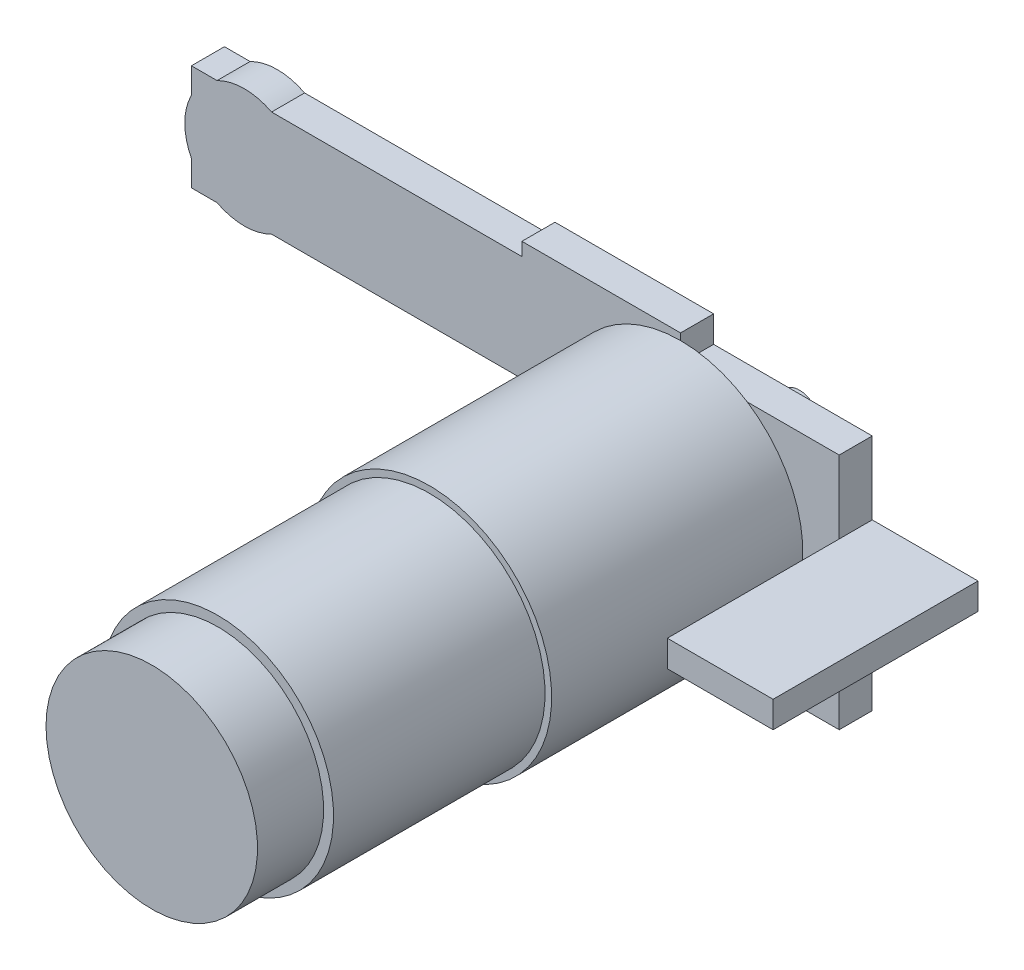
SolidWorks part; units mm, degrees
ref_plane "Front Plane" through (0, 0, 0) normal (0, 0, 1) x (1, 0, 0)
ref_plane "Top Plane" through (0, 0, 0) normal (0, 1, 0) x (1, 0, 0)
ref_plane "Right Plane" through (0, 0, 0) normal (1, 0, 0) x (0, 0, -1)
ref_plane "PL_Y_20p50" through (0, 20.5, 0) normal (0, 1, 0) x (1, 0, 0)
sketch "SK_P01_Gearmotor37Dwith64CPRenc" plane through (0, 20.5, 0) normal (0, 1, 0) x (1, 0, 0)
  line L0 (17.5, 49) -> (20.5, 49)
  line L1 (20.5, 49) -> (20.5, 31)
  line L2 (20.5, 31) -> (36, 31)
  line L3 (36, 31) -> (36, -7)
  line L4 (36, -7) -> (35, -7)
  line L5 (35, -7) -> (35, -39)
  line L6 (35, -39) -> (33.5, -39)
  line L7 (33.5, -39) -> (33.5, -49)
  line L8 (33.5, -49) -> (17.5, -49)
  line L9 (17.5, -49) -> (17.5, 49)
  line L10 (17.5, 54) -> (17.5, -54) construction
revolve "P01_Gearmotor37Dwith64CPRenc" add sketch "SK_P01_Gearmotor37Dwith64CPRenc" angle 360 about L10
sketch "SK_P02_Moduleplate" plane through (0, 0, 0) normal (0, 1, 0) x (1, 0, 0)
  line L0 (-6.5, 31) -> (17.5, 31)
  line L1 (17.5, 31) -> (17.5, 36)
  line L2 (17.5, 36) -> (-6.5, 36)
  line L3 (-6.5, 36) -> (-6.5, 31)
extrude "P02_Moduleplate" add sketch "SK_P02_Moduleplate" along normal blind 40
sketch "SK_P03_Moduleplate" plane through (0, 0, 0) normal (0, 1, 0) x (1, 0, 0)
  line L0 (17.5, 31) -> (41.5, 31)
  line L1 (41.5, 31) -> (41.5, 36)
  line L2 (41.5, 36) -> (17.5, 36)
  line L3 (17.5, 36) -> (17.5, 31)
extrude "P03_Moduleplate" add sketch "SK_P03_Moduleplate" along normal blind 36
sketch "SK_P04_Trailingarm" plane through (0, 0, 0) normal (0, 1, 0) x (1, 0, 0)
  line L0 (-56.5, 31) -> (-6.5, 31)
  line L1 (-6.5, 31) -> (-6.5, 36)
  line L2 (-6.5, 36) -> (-56.5, 36)
  line L3 (-56.5, 36) -> (-56.5, 31)
extrude "P04_Trailingarm" add sketch "SK_P04_Trailingarm" along normal blind 16 from offset 22
sketch "SK_P05_Pivotboss" plane through (0, 0, 0) normal (0, 0, 1) x (1, 0, 0)
  circle A0 centre (-48.5, 30) radius 9
extrude "P05_Pivotboss" add sketch "SK_P05_Pivotboss" along normal blind 5 from offset 36
sketch "SK_P06_Springtab" plane through (0, 0, 0) normal (0, 1, 0) x (1, 0, 0)
  line L0 (41.5, 5) -> (57.5, 5)
  line L1 (57.5, 5) -> (57.5, 36)
  line L2 (57.5, 36) -> (41.5, 36)
  line L3 (41.5, 36) -> (41.5, 5)
extrude "P06_Springtab" add sketch "SK_P06_Springtab" along normal blind 4 from offset 21
